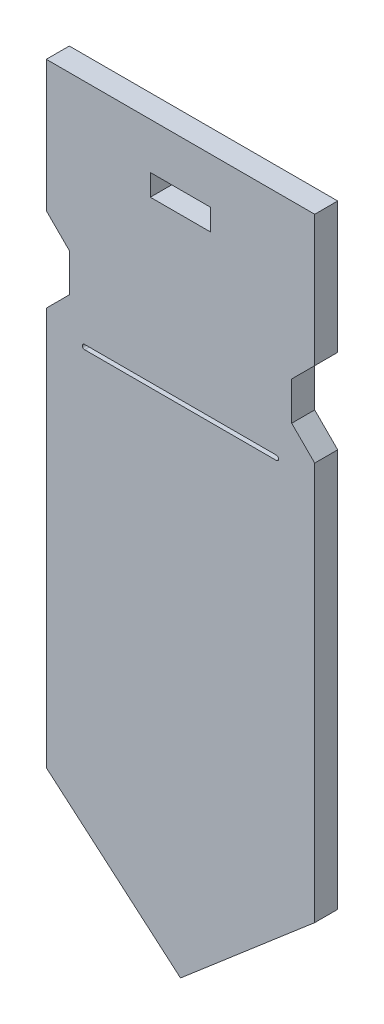
SolidWorks part; units mm, degrees
ref_plane "Front Plane" through (0, 0, 0) normal (0, 0, 1) x (1, 0, 0)
ref_plane "Top Plane" through (0, 0, 0) normal (0, 1, 0) x (1, 0, 0)
ref_plane "Right Plane" through (0, 0, 0) normal (1, 0, 0) x (0, 0, -1)
sketch "Esboço1" plane through (0, 0, 0) normal (0, 0, 1) x (1, 0, 0)
  line L0 (35, -80) -> (17.5, -95)
  line L1 (0, 0) -> (35, 0)
  line L2 (0, 0) -> (0, -95)
  line L3 (0, -95) -> (35, -95)
  line L4 (35, 0) -> (35, -95)
  line L5 (17.5, -95) -> (0, -80)
  line L6 (5, -30) -> (30, -30) construction
  line L7 (5, -29.7) -> (30, -29.7)
  line L8 (5, -30.3) -> (30, -30.3)
  line L9 (0, -28.1) -> (3, -25.1)
  line L10 (13.563, -6) -> (21.437, -6)
  line L11 (13.563, -6) -> (13.563, -8.794)
  line L12 (13.563, -8.794) -> (21.437, -8.794)
  line L13 (21.437, -6) -> (21.437, -8.794)
  line L14 (3, -25.1) -> (3, -20.1)
  line L15 (3, -20.1) -> (0, -17.1)
  line L16 (17.5, 0) -> (17.5, -75.1665) construction
  line L17 (35, -28.1) -> (32, -25.1)
  line L18 (32, -25.1) -> (32, -20.1)
  line L19 (32, -20.1) -> (35, -17.1)
  arc A0 (5, -29.7) -> (5, -30.3) centre (5, -30) ccw
  arc A1 (30, -30.3) -> (30, -29.7) centre (30, -30) ccw
  point P10 (17.5, -30)
  dimension "D8" = 0.3
  dimension "D1" = 35
  dimension "D2" = 95
  dimension "D3" = 15
  dimension "D4" = 15
  dimension "D5" = 17.5
  dimension "D6" = 30
  dimension "D7" = 25
  dimension "D9" = 7.874
  dimension "D10" = 2.794
  dimension "D11" = 13.563
  dimension "D12" = 6
  dimension "D13" = 45
  dimension "D14" = 5
  dimension "D15" = 11
  dimension "D16" = 17.1
extrude "Ressalto-extrusão1" add sketch "Esboço1" along normal blind 3 contours L5 L0 L4 L1 L2 A1 L8 A0 L7 L10 L13 L12 L11
